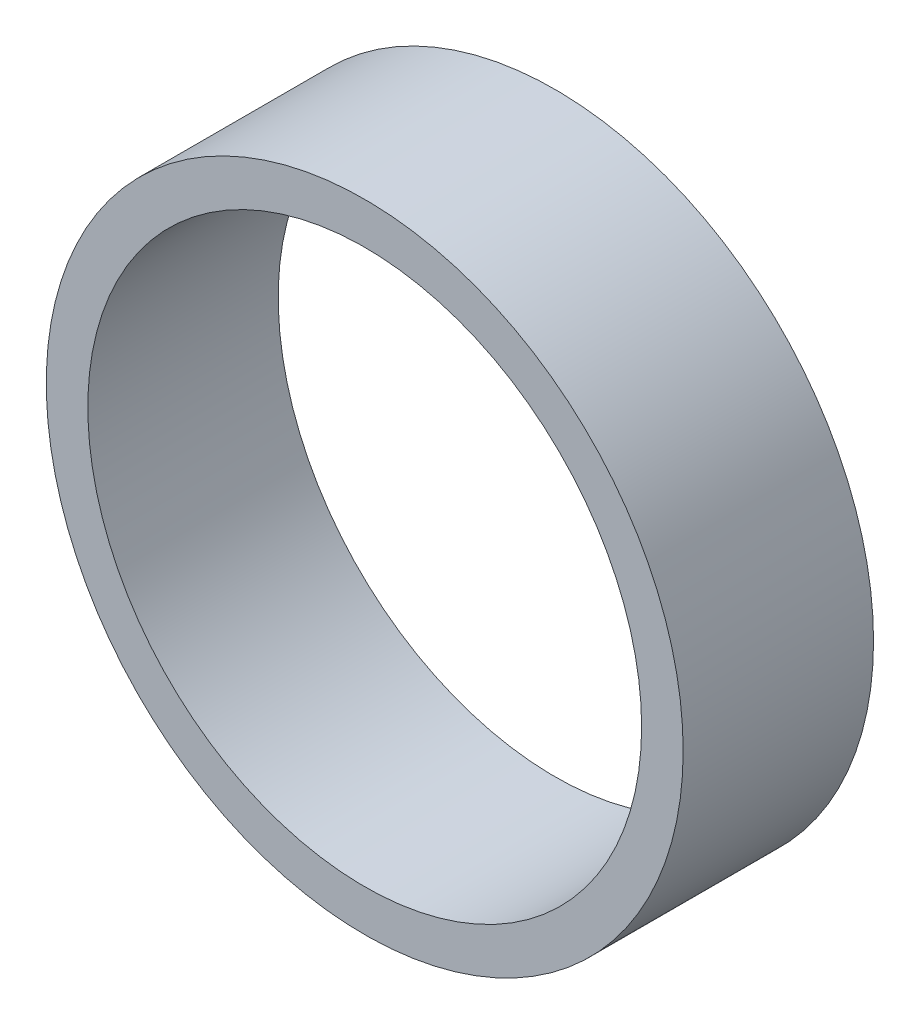
SolidWorks part; units mm, degrees
ref_plane "Front" through (0, 0, 0) normal (0, 0, 1) x (1, 0, 0)
ref_plane "Top" through (0, 0, 0) normal (0, 1, 0) x (1, 0, 0)
ref_plane "Right" through (0, 0, 0) normal (1, 0, 0) x (0, 0, -1)
sketch "Эскиз1" plane through (0, 0, 0) normal (0, 0, 1) x (1, 0, 0)
  circle A0 centre (0, 0) radius 8
  circle A1 centre (0, 0) radius 9.2
extrude "Бобышка-Вытянуть1" add sketch "Эскиз1" along normal blind 5.5
